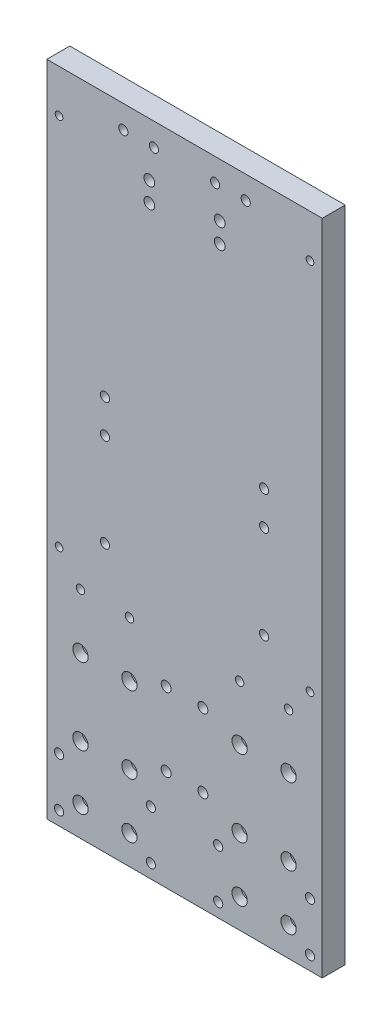
SolidWorks part; units mm, degrees
material "3.3545 (EN-AW 5086)"
ref_plane "Ebene vorne" through (0, 0, 0) normal (0, 0, 1) x (1, 0, 0)
ref_plane "Ebene oben" through (0, 0, 0) normal (0, 1, 0) x (1, 0, 0)
ref_plane "Ebene rechts" through (0, 0, 0) normal (1, 0, 0) x (0, 0, -1)
sketch "Skizze1" plane through (0, 0, 0) normal (0, 0, 1) x (1, 0, 0)
  line L0 (0, 0) -> (0, 306.9421) construction
  line L1 (-90, 0) -> (90, 0)
  line L2 (-90, 0) -> (-90, 430)
  line L3 (-90, 430) -> (90, 430)
  line L4 (90, 0) -> (90, 430)
  dimension "D1" = 430
  dimension "D2" = 180
extrude "Aufsatz-Linear austragen1" add sketch "Skizze1" along normal blind 15
sketch "Skizze2" plane through (0, 0, 15) normal (0, 0, 1) x (1, 0, 0)
  line L0 (0, 0) -> (0, 132.3712) construction
  line L1 (0, 37) -> (108.2524, 37) construction
  line L2 (36, 19) -> (68, 19) construction
  line L3 (-90, 0) -> (90, 0) construction
  line L4 (0, 80) -> (116.6417, 80) construction
  line L5 (36, 141) -> (68, 141) construction
  circle A0 centre (36, 19) radius 2.75
  circle A1 centre (68, 19) radius 2.75
  circle A2 centre (68, 55) radius 2.75
  circle A3 centre (36, 55) radius 2.75
  circle A4 centre (-36, 19) radius 2.75
  circle A5 centre (-68, 19) radius 2.75
  circle A6 centre (-68, 55) radius 2.75
  circle A7 centre (-36, 55) radius 2.75
  circle A8 centre (-36, 105) radius 2.75
  circle A9 centre (-68, 105) radius 2.75
  circle A10 centre (-68, 141) radius 2.75
  circle A11 centre (-36, 141) radius 2.75
  circle A12 centre (36, 105) radius 2.75
  circle A13 centre (68, 105) radius 2.75
  circle A14 centre (68, 141) radius 2.75
  circle A15 centre (36, 141) radius 2.75
  dimension "D1" = 72
  dimension "D2" = 32
  dimension "D3" = 36
  dimension "D5" = 5.5
  dimension "D4" = 19
  dimension "D6" = 105
extrude "Schnitt-Linear austragen1" cut sketch "Skizze2" against normal blind 40
sketch "Skizze3" plane through (0, 0, 15) normal (0, 0, 1) x (1, 0, 0)
  line L0 (0, 0) -> (0, 203.365) construction
  line L1 (12, 66) -> (12, 114) construction
  line L2 (12, 90) -> (-23.9233, 90) construction
  line L3 (-90, 0) -> (90, 0) construction
  circle A0 centre (12, 66) radius 3.25
  circle A1 centre (12, 114) radius 3.25
  circle A2 centre (-12, 114) radius 3.25
  circle A3 centre (-12, 66) radius 3.25
  dimension "D1" = 6.5
  dimension "D2" = 24
  dimension "D3" = 48
  dimension "D4" = 90
extrude "Schnitt-Linear austragen2" cut sketch "Skizze3" against normal blind 40
sketch "Skizze6" plane through (0, 0, 0) normal (0, 0, -1) x (-1, 0, 0)
  line L0 (0, 0) -> (0, 489.1214) construction
  line L1 (-35, 388.5) -> (-9.982, 388.5) construction
  line L2 (-90, 430) -> (90, 430) construction
  circle A0 centre (23, 395) radius 3.5
  circle A1 centre (23, 382) radius 3.5
  circle A2 centre (-23, 382) radius 3.5
  circle A3 centre (-23, 395) radius 3.5
  dimension "D1" = 46
  dimension "D2" = 13
  dimension "D3" = 7
  dimension "D4" = 35
extrude "Schnitt-Linear austragen5" cut sketch "Skizze6" against normal blind 30
sketch "Skizze7" plane through (0, 0, 15) normal (0, 0, 1) x (1, 0, 0)
  line L0 (0, 0) -> (0, 444.8684) construction
  line L1 (20, 415) -> (40, 415) construction
  line L2 (90, 430) -> (-90, 430) construction
  circle A0 centre (20, 415) radius 3
  circle A1 centre (40, 415) radius 3
  circle A2 centre (-40, 415) radius 3
  circle A3 centre (-20, 415) radius 3
  dimension "6" = 6
  dimension "D2" = 40
  dimension "D3" = 80
  dimension "D4" = 15
extrude "Schnitt-Linear austragen6" cut sketch "Skizze7" against normal blind 40
sketch "Skizze8" plane through (0, 0, 0) normal (0, 0, -1) x (-1, 0, 0)
  line L0 (0, 0) -> (0, 198.7577) construction
  line L1 (22, 9) -> (82, 9) construction
  line L2 (22, 9) -> (22, 41) construction
  line L3 (22, 41) -> (82, 41) construction
  line L4 (82, 41) -> (82, 9) construction
  line L5 (90, 0) -> (-90, 0) construction
  circle A0 centre (22, 9) radius 3
  circle A1 centre (82, 9) radius 3
  circle A2 centre (22, 41) radius 3
  circle A3 centre (82, 41) radius 3
  circle A4 centre (-82, 41) radius 3
  circle A5 centre (-82, 9) radius 3
  circle A6 centre (-22, 9) radius 3
  circle A7 centre (-22, 41) radius 3
  dimension "D5" = 6
  dimension "D1" = 9
  dimension "D2" = 32
  dimension "D3" = 22
  dimension "D4" = 82
extrude "Schnitt-Linear austragen7" cut sketch "Skizze8" against normal blind 40
sketch "Skizze9" plane through (0, 0, 15) normal (0, 0, 1) x (1, 0, 0)
  line L0 (0, 0) -> (0, 95.481) construction
  circle A0 centre (68, 55) radius 5
  circle A1 centre (68, 19) radius 5
  circle A2 centre (36, 19) radius 5
  circle A3 centre (36, 55) radius 5
  circle A4 centre (-68, 19) radius 5
  circle A5 centre (-36, 19) radius 5
  circle A6 centre (-68, 55) radius 5
  circle A7 centre (-36, 55) radius 5
  circle A8 centre (68, 105) radius 5
  circle A9 centre (36, 105) radius 5
  circle A10 centre (-36, 105) radius 5
  circle A11 centre (-68, 105) radius 5
  dimension "D1" = 10
extrude "Schnitt-Linear austragen8" cut sketch "Skizze9" against normal blind 6
sketch "Skizze11" plane through (0, 0, 0) normal (0, 0, -1) x (-1, 0, 0)
  line L0 (0, 0) -> (0, 437.261) construction
  line L1 (-52, 175) -> (-52, 236) construction
  line L2 (-90, 0) -> (-90, 430) construction
  line L3 (90, 0) -> (-90, 0) construction
  line L4 (-52, 236) -> (-52, 258) construction
  circle A0 centre (-52, 175) radius 3
  circle A1 centre (-52, 236) radius 3
  circle A2 centre (52, 236) radius 3
  circle A3 centre (52, 175) radius 3
  circle A4 centre (-52, 258) radius 3
  circle A5 centre (52, 258) radius 3
  dimension "D5" = 6
  dimension "D6" = 258
  dimension "D1" = 38
  dimension "D2" = 175
  dimension "D3" = 236
  dimension "D4" = 61
extrude "Schnitt-Linear austragen10" cut sketch "Skizze11" against normal blind 40
sketch "Skizze10" plane through (0, 0, 0) normal (0, 0, -1) x (-1, 0, 0)
  circle A0 centre (12, 114) radius 5.5
  circle A1 centre (-12, 114) radius 5.5
  circle A2 centre (52, 175) radius 5.5
  circle A3 centre (-52, 175) radius 5.5
  dimension "D1" = 11
extrude "Schnitt-Linear austragen9" cut sketch "Skizze10" against normal blind 7
sketch "Skizze12" plane through (0, 0, 0) normal (0, 0, -1) x (-1, 0, 0)
  line L0 (0, 0) -> (0, 437.261) construction
  line L1 (82, 402) -> (82, 158) construction
  line L2 (90, 430) -> (90, 0) construction
  line L4 (-90, 430) -> (90, 430) construction
  circle A0 centre (82, 402) radius 2.5
  circle A1 centre (82, 158) radius 2.5
  circle A2 centre (-82, 158) radius 2.5
  circle A3 centre (-82, 402) radius 2.5
  dimension "D3" = 5
  dimension "D1" = 8
  dimension "D2" = 28
  dimension "D4" = 272
extrude "Schnitt-Linear austragen11" cut sketch "Skizze12" against normal blind 30
